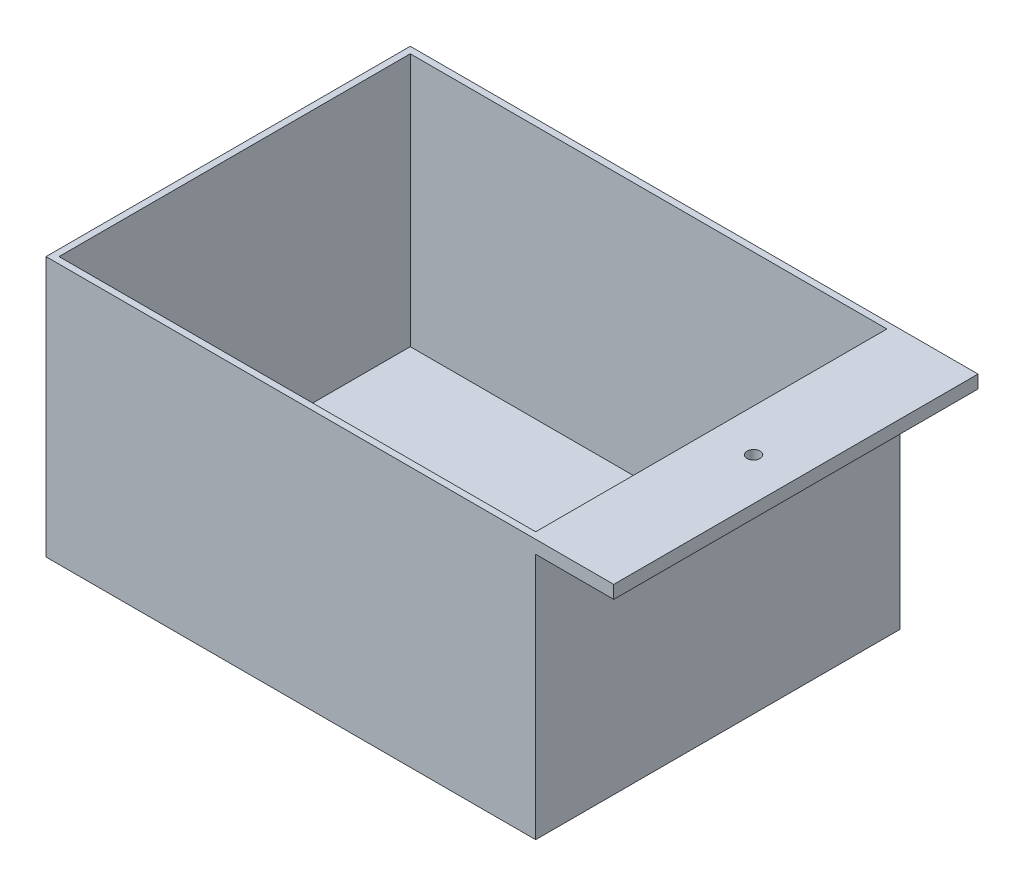
SolidWorks part; units mm, degrees
ref_plane "Front Plane" through (0, 0, 0) normal (0, 0, 1) x (1, 0, 0)
ref_plane "Top Plane" through (0, 0, 0) normal (0, 1, 0) x (1, 0, 0)
ref_plane "Right Plane" through (0, 0, 0) normal (1, 0, 0) x (0, 0, -1)
sketch "Sketch1" plane through (0, 0, 0) normal (0, 1, 0) x (1, 0, 0)
  line L1 (-119.507, 88.9) -> (119.507, 88.9)
  line L2 (-119.507, 88.9) -> (-119.507, -88.9)
  line L3 (-119.507, -88.9) -> (119.507, -88.9)
  line L4 (119.507, 88.9) -> (119.507, -88.9)
  line L5 (-119.507, 88.9) -> (119.507, -88.9) construction
  line L6 (-119.507, -88.9) -> (119.507, 88.9) construction
  point P0 (0, 0)
  dimension "D1" = 177.8
  dimension "D2" = 239.014
extrude "Boss-Extrude1" add sketch "Sketch1" along normal blind 127
sketch "Sketch2" plane through (0, 127, 0) normal (0, 1, 0) x (1, 0, 0)
  line L1 (-116.332, 85.725) -> (116.332, 85.725)
  line L2 (-116.332, 85.725) -> (-116.332, -85.725)
  line L3 (-116.332, -85.725) -> (116.332, -85.725)
  line L4 (116.332, 85.725) -> (116.332, -85.725)
  line L5 (-116.332, 85.725) -> (116.332, -85.725) construction
  line L6 (-116.332, -85.725) -> (116.332, 85.725) construction
  point P0 (0, 0)
  dimension "D1" = 232.664
  dimension "D2" = 171.45
extrude "Cut-Extrude1" cut sketch "Sketch2" against normal blind 123.825
sketch "Sketch3" plane through (119.507, 0, 0) normal (1, 0, 0) x (0, 0, -1)
  line L0 (88.9, 127) -> (88.9, 0) construction
  line L1 (-88.9, 127) -> (88.9, 127)
  line L2 (-88.9, 127) -> (-88.9, 120.65)
  line L3 (-88.9, 120.65) -> (88.9, 120.65)
  line L4 (88.9, 127) -> (88.9, 120.65)
  dimension "D1" = 6.35
extrude "Boss-Extrude2" add sketch "Sketch3" along normal blind 38.1
sketch "Sketch5" plane through (0, 127, 0) normal (0, 1, 0) x (1, 0, 0)
  line L0 (116.332, 0) -> (157.607, 0) construction
  line L1 (116.332, -85.725) -> (116.332, 85.725) construction
  line L2 (157.607, 88.9) -> (157.607, -88.9) construction
  circle A0 centre (136.9695, 0) radius 3.175
  dimension "D1" = 6.35
extrude "Cut-Extrude2" cut sketch "Sketch5" against normal up to surface (6.35 mm away) up to face at (138.557, 120.65, 0)
